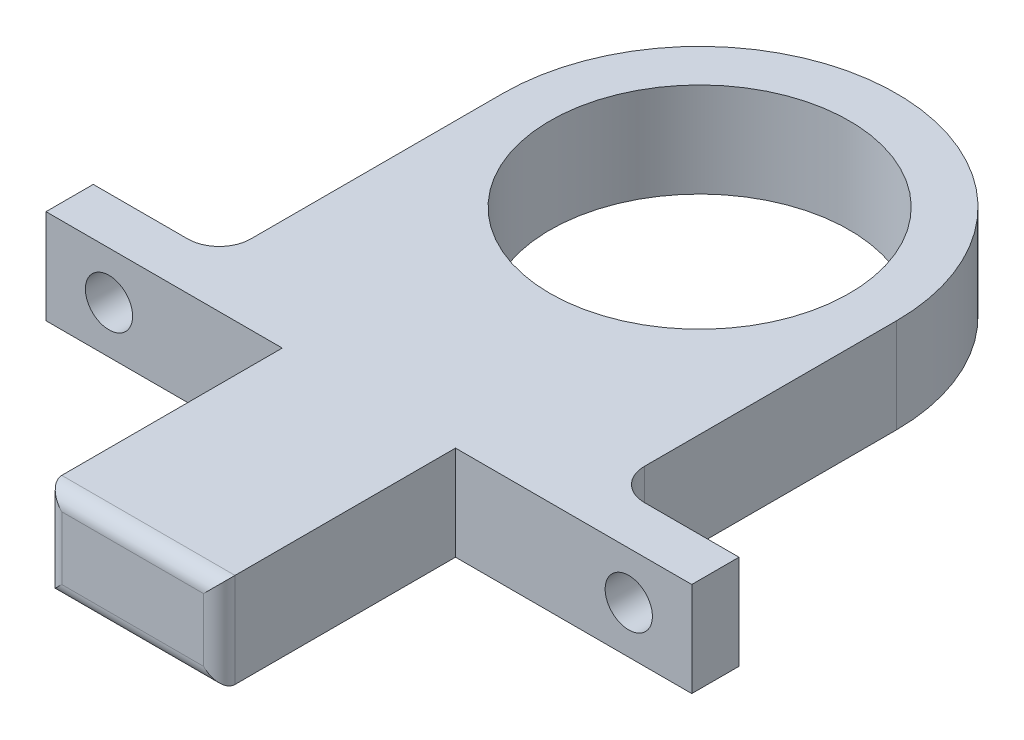
SolidWorks part; units mm, degrees
ref_plane "Alzado" through (0, 0, 0) normal (0, 0, 1) x (1, 0, 0)
ref_plane "Planta" through (0, 0, 0) normal (0, 1, 0) x (1, 0, 0)
ref_plane "Vista lateral" through (0, 0, 0) normal (1, 0, 0) x (0, 0, -1)
sketch "Croquis1" plane through (0, 0, 0) normal (0, 1, 0) x (1, 0, 0)
  line L0 (-12.5, 0) -> (12.5, 0) construction
  line L1 (-12.5, 0) -> (-12.5, -16)
  line L2 (-12.5, -21) -> (12.5, -21)
  line L3 (12.5, -16) -> (12.5, 0)
  line L4 (-20.5, -18) -> (20.5, -18) construction
  line L6 (-20.5, -18) -> (-14.5, -18)
  line L7 (-20.5, -18) -> (-20.5, -21)
  line L8 (-20.5, -21) -> (-12.5, -21)
  line L9 (-12.5, -14) -> (-12.5, -21)
  line L10 (20.5, -18) -> (14.5, -18)
  line L11 (20.5, -18) -> (20.5, -21)
  line L12 (20.5, -21) -> (12.5, -21)
  line L13 (12.5, -14) -> (12.5, -21)
  line L14 (-5.5, -21) -> (5.5, -21)
  line L15 (-5.5, -21) -> (-5.5, -36)
  line L16 (-5.5, -36) -> (5.5, -36)
  line L17 (5.5, -21) -> (5.5, -36)
  circle A0 centre (0, 0) radius 12.5
  circle A1 centre (0, 0) radius 9.5
  arc A2 (14.5, -18) -> (12.5, -16) centre (14.5, -16) cw
  arc A3 (-14.5, -18) -> (-12.5, -16) centre (-14.5, -16) ccw
  dimension "D1" = 25
  dimension "D2" = 19
  dimension "D6" = 2
  dimension "D3" = 21
  dimension "D4" = 3
  dimension "D5" = 8
  dimension "D7" = 8
  dimension "D8" = 25
  dimension "D9" = 12.5
  dimension "D10" = 11
  dimension "D11" = 15
  dimension "D12" = 5.5
extrude "Saliente-Extruir1" add sketch "Croquis1" along normal blind 6
sketch "Croquis2" plane through (0, 0, 21) normal (0, 0, 1) x (1, 0, 0)
  line L0 (-20.5, 3) -> (20.5, 3) construction
  line L1 (-20.5, 6) -> (-20.5, 0) construction
  line L2 (20.5, 6) -> (20.5, 0) construction
  circle A0 centre (-16.5, 3) radius 1.5
  circle A1 centre (16.5, 3) radius 1.5
  dimension "D3" = 3
  dimension "D4" = 3
  dimension "D1" = 4
  dimension "D2" = 4
extrude "Cortar-Extruir1" cut sketch "Croquis2" against normal blind 6
sketch "Croquis3" plane through (0, 0, 18) normal (0, 0, -1) x (-1, 0, 0)
  circle A0 centre (-16.5, 3) radius 3
  circle A1 centre (16.5, 3) radius 3
  dimension "D1" = 6
  dimension "D2" = 6
extrude "Cortar-Extruir2" cut sketch "Croquis3" along normal blind 6
fillet "Redondeo1" radius 1 4 edges at (5.5, 3, 36) (-5.5, 3, 36) (0, 0, 36) (0, 6, 36)
